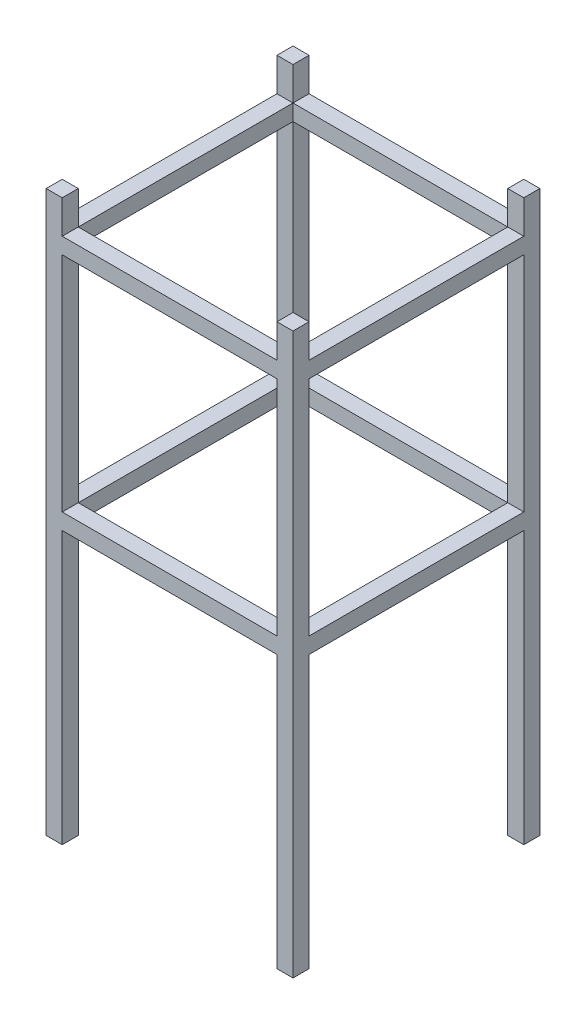
SolidWorks part; units mm, degrees
ref_plane "Front Plane" through (0, 0, 0) normal (0, 0, 1) x (1, 0, 0)
ref_plane "Top Plane" through (0, 0, 0) normal (0, 1, 0) x (1, 0, 0)
ref_plane "Right Plane" through (0, 0, 0) normal (1, 0, 0) x (0, 0, -1)
sketch "Sketch2" plane through (0, 0, 0) normal (0, 1, 0) x (1, 0, 0)
  line L0 (-50, 0) -> (50, 0) construction
  line L1 (0, -55) -> (0, 55) construction
  line L2 (0, -50) -> (0, 50) construction
  line L3 (-55, 0) -> (55, 0) construction
  line L5 (-50, 50) -> (50, 50) construction
  line L6 (-50, 50) -> (-50, -50) construction
  line L7 (-50, -50) -> (50, -50) construction
  line L8 (50, 50) -> (50, -50) construction
  point P6 (0, 0)
  point P11 (0, 0)
sketch "Sketch3" plane through (0, 0, 0) normal (0, 1, 0) x (1, 0, 0)
  line L0 (0, -55) -> (0, 55) construction
  line L1 (-50, 50) -> (-43.5, 50)
  line L2 (-50, 50) -> (-50, 43.5)
  line L3 (-50, 43.5) -> (-43.5, 43.5)
  line L4 (-43.5, 50) -> (-43.5, 43.5)
  line L5 (50, 43.5) -> (43.5, 43.5)
  line L6 (43.5, 50) -> (43.5, 43.5)
  line L7 (50, 50) -> (43.5, 50)
  line L8 (50, 50) -> (50, 43.5)
  line L9 (-55, 0) -> (55, 0) construction
  line L10 (50, -50) -> (50, -43.5)
  line L11 (50, -50) -> (43.5, -50)
  line L12 (43.5, -50) -> (43.5, -43.5)
  line L13 (50, -43.5) -> (43.5, -43.5)
  line L14 (-50, -43.5) -> (-43.5, -43.5)
  line L15 (-43.5, -50) -> (-43.5, -43.5)
  line L16 (-50, -50) -> (-43.5, -50)
  line L17 (-50, -50) -> (-50, -43.5)
extrude "Boss-Extrude1" add sketch "Sketch3" along normal blind 200
sketch "Sketch11" plane through (0, 200, 0) normal (0, 1, 0) x (1, 0, 0)
  line L1 (-43.5, 43.5) -> (43.5, 43.5)
  line L2 (-43.5, 43.5) -> (-43.5, -43.5)
  line L3 (-43.5, -43.5) -> (43.5, -43.5)
  line L4 (43.5, 43.5) -> (43.5, -43.5)
  line L5 (-50, 50) -> (50, 50)
  line L6 (-50, 50) -> (-50, -50)
  line L7 (-50, -50) -> (50, -50)
  line L8 (50, 50) -> (50, -50)
extrude "Boss-Extrude7" add sketch "Sketch11" against normal blind 6.5
sketch "Sketch12" plane through (0, 200, 0) normal (0, 1, 0) x (1, 0, 0)
  line L1 (-43.5, 43.5) -> (43.5, 43.5)
  line L2 (-43.5, 43.5) -> (-43.5, -43.5)
  line L3 (-43.5, -43.5) -> (43.5, -43.5)
  line L4 (43.5, 43.5) -> (43.5, -43.5)
  line L5 (-50, 50) -> (50, 50)
  line L6 (-50, 50) -> (-50, -50)
  line L7 (-50, -50) -> (50, -50)
  line L8 (50, 50) -> (50, -50)
extrude "Boss-Extrude8" add sketch "Sketch12" along normal blind 3.25 and the other way blind 3.25 from offset 100 offset against normal yes
sketch "Sketch13" plane through (0, 200, 0) normal (0, 1, 0) x (1, 0, 0)
  line L0 (0, -55) -> (0, 55) construction
  line L1 (-50, 50) -> (-43.5, 50)
  line L2 (-50, 50) -> (-50, 43.5)
  line L3 (-50, 43.5) -> (-43.5, 43.5)
  line L4 (-43.5, 50) -> (-43.5, 43.5)
  line L5 (50, 43.5) -> (43.5, 43.5)
  line L6 (43.5, 50) -> (43.5, 43.5)
  line L7 (50, 50) -> (43.5, 50)
  line L8 (50, 50) -> (50, 43.5)
  line L9 (-55, 0) -> (55, 0) construction
  line L10 (50, -50) -> (50, -43.5)
  line L11 (50, -50) -> (43.5, -50)
  line L12 (43.5, -50) -> (43.5, -43.5)
  line L13 (50, -43.5) -> (43.5, -43.5)
  line L14 (-50, -43.5) -> (-43.5, -43.5)
  line L15 (-43.5, -50) -> (-43.5, -43.5)
  line L16 (-50, -50) -> (-43.5, -50)
  line L17 (-50, -50) -> (-50, -43.5)
extrude "Boss-Extrude9" add sketch "Sketch13" along normal blind 13.5
sketch "Sketch14" plane through (0, 0, 0) normal (0, -1, 0) x (1, 0, 0)
  line L0 (0, -55) -> (0, 55) construction
  line L1 (-50, 50) -> (-43.5, 50)
  line L2 (-50, 50) -> (-50, 43.5)
  line L3 (-50, 43.5) -> (-43.5, 43.5)
  line L4 (-43.5, 50) -> (-43.5, 43.5)
  line L5 (50, 43.5) -> (43.5, 43.5)
  line L6 (43.5, 50) -> (43.5, 43.5)
  line L7 (50, 50) -> (43.5, 50)
  line L8 (50, 50) -> (50, 43.5)
  line L9 (55, 0) -> (-55, 0) construction
  line L10 (50, -50) -> (50, -43.5)
  line L11 (50, -50) -> (43.5, -50)
  line L12 (43.5, -50) -> (43.5, -43.5)
  line L13 (50, -43.5) -> (43.5, -43.5)
  line L14 (-50, -43.5) -> (-43.5, -43.5)
  line L15 (-43.5, -50) -> (-43.5, -43.5)
  line L16 (-50, -50) -> (-43.5, -50)
  line L17 (-50, -50) -> (-50, -43.5)
extrude "Boss-Extrude10" add sketch "Sketch14" along normal blind 13.5
